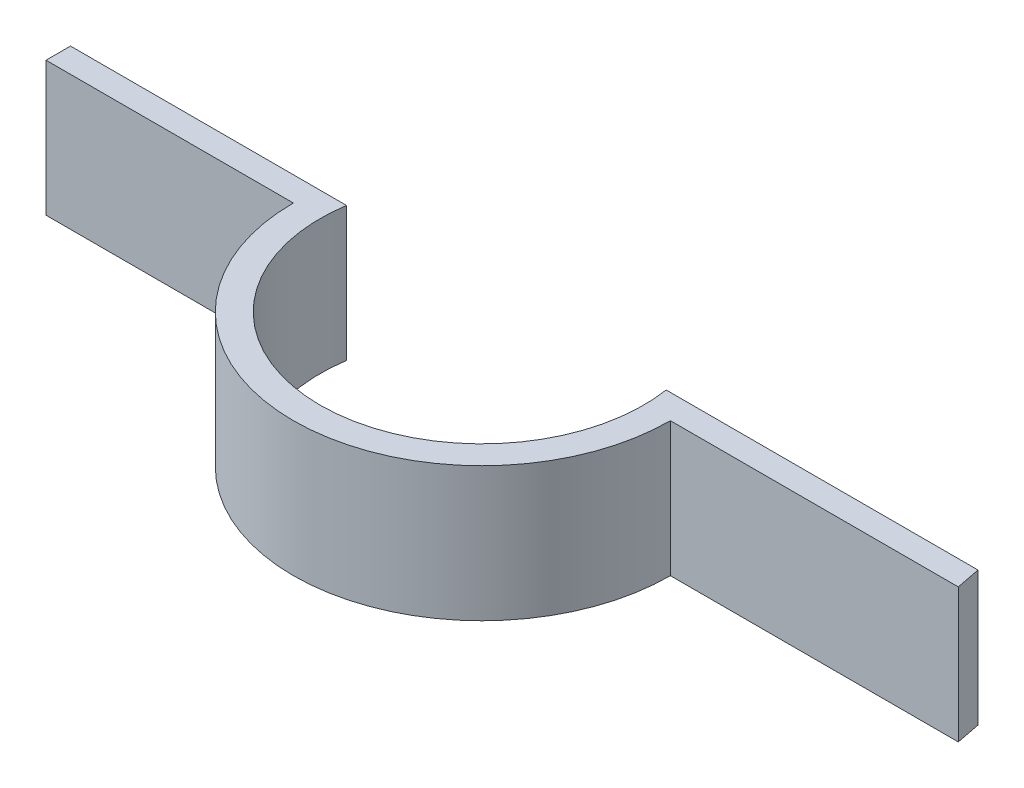
SolidWorks part; units mm, degrees
ref_plane "Front Plane" through (0, 0, 0) normal (0, 0, 1) x (1, 0, 0)
ref_plane "Top Plane" through (0, 0, 0) normal (0, 1, 0) x (1, 0, 0)
ref_plane "Right Plane" through (0, 0, 0) normal (1, 0, 0) x (0, 0, -1)
sketch "Sketch1" plane through (0, 0, 0) normal (0, 1, 0) x (1, 0, 0)
  line L0 (-7.0199, 0) -> (-16.2317, 0)
  line L1 (-16.2317, 0) -> (-16.2317, 0.9122)
  line L2 (-16.2317, 0.9122) -> (-5.9519, 0.9122)
  line L3 (7.0199, 0) -> (17.7415, 0)
  line L4 (17.7415, 0) -> (17.5633, 0.9122)
  line L5 (17.5633, 0.9122) -> (5.9519, 0.9122)
  arc A0 (-5.9519, 0.9122) -> (5.9519, 0.9122) centre (0, 0) ccw
  arc A1 (-7.0199, 0) -> (7.0199, 0) centre (0, 0) ccw
extrude "Boss-Extrude2" add sketch "Sketch1" along normal blind 5
